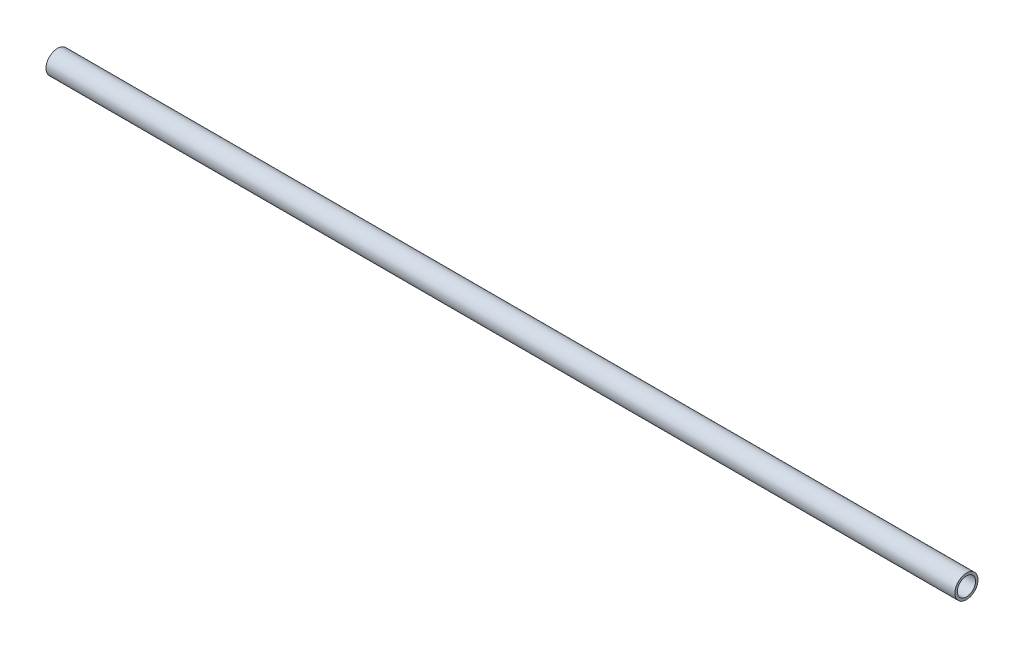
SolidWorks part; units mm, degrees
ref_plane "Front Plane" through (0, 0, 0) normal (1, 0, 0) x (0, 1, 0)
ref_plane "Top Plane" through (0, 0, 0) normal (0, 0, 1) x (0, 1, 0)
ref_plane "Right Plane" through (0, 0, 0) normal (0, 1, 0) x (-1, 0, 0)
sketch "Sketch1" plane through (0, 0, 0) normal (1, 0, 0) x (0, 1, 0)
  circle A0 centre (0, 0) radius 6.35
  circle A1 centre (0, 0) radius 5
  dimension "D1" = 12.7
  dimension "D2" = 10
extrude "Boss-Extrude1" add sketch "Sketch1" along normal blind 500
